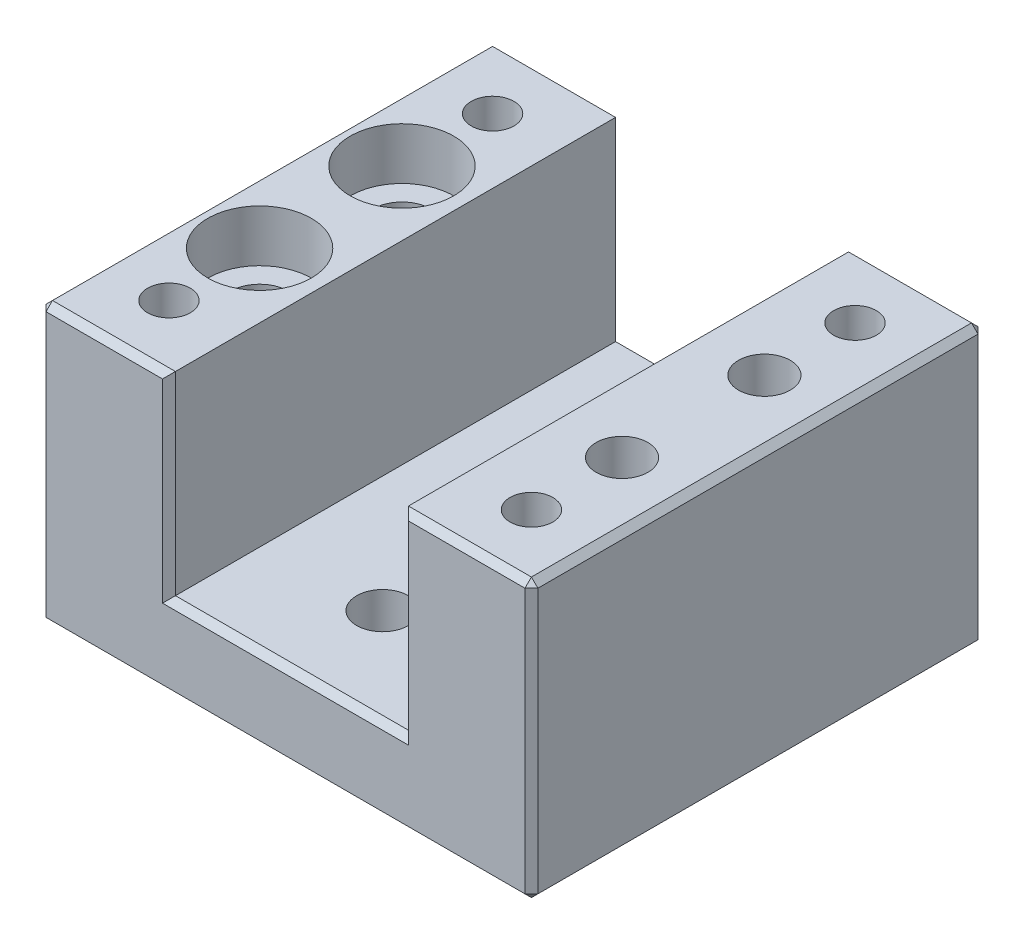
SolidWorks part; units mm, degrees
ref_plane "前视基准面" through (0, 0, 0) normal (0, 0, 1) x (1, 0, 0)
ref_plane "上视基准面" through (0, 0, 0) normal (0, 1, 0) x (1, 0, 0)
ref_plane "右视基准面" through (0, 0, 0) normal (1, 0, 0) x (0, 0, -1)
sketch "草图1" plane through (0, 0, 0) normal (0, 0, 1) x (1, 0, 0)
  line L1 (0, 0) -> (38, 0)
  line L2 (0, 0) -> (0, 6.45)
  line L3 (0, 6.45) -> (38, 6.45)
  line L4 (38, 0) -> (38, 6.45)
  dimension "D1" = 6.45
  dimension "D2" = 38
extrude "凸台-拉伸1" add sketch "草图1" along normal blind 35
sketch "草图2" plane through (0, 6.45, 0) normal (0, 1, 0) x (1, 0, 0)
  line L0 (38, -35) -> (0, -35) construction
  line L1 (0, 0) -> (10, 0)
  line L2 (0, 0) -> (0, -35)
  line L3 (0, -35) -> (10, -35)
  line L4 (10, 0) -> (10, -35)
  line L6 (38, -35) -> (28, -35)
  line L7 (38, -35) -> (38, 0)
  line L8 (38, 0) -> (28, 0)
  line L9 (28, -35) -> (28, 0)
  dimension "D1" = 10
  dimension "D2" = 10
extrude "凸台-拉伸2" add sketch "草图2" along normal blind 15
hole_wizard "M4 六角凹头螺钉的柱形沉头孔1" positions "草图4" profile "草图3" counterbore size "M4" standard "ISO" end condition through all
sketch "草图4" plane through (0, 21.45, 0) normal (0, 1, 0) x (-1, 0, 0)
  line L0 (0, 35) -> (-10, 35) construction
  line L1 (0, 0) -> (0, 35) construction
  point P0 (-5, 23)
  dimension "D1" = 12
  dimension "D2" = 5
sketch "草图3" plane through (5, 21.45, 23) normal (1, 0, 0) x (0, 0, 1)
  line L0 (0, 0) -> (0, 21.45)
  line L1 (0, 21.45) -> (2.25, 21.45)
  line L3 (2.25, 21.45) -> (2.25, 4)
  line L4 (2.25, 4) -> (4, 4)
  line L5 (4, 4) -> (4, 0)
  line L7 (4, 0) -> (0, 0)
  line L11 (0, -6.35) -> (0, 107.95) construction
  dimension "通孔孔直径" = 4.5
  dimension "通孔孔深度" = 21.45
  dimension "柱形沉头孔直径" = 8
  dimension "柱形沉头孔深度" = 4
pattern_linear "阵列(线性)1" count 2 spacing 11 along (0, 0, -1) of "M4 六角凹头螺钉的柱形沉头孔1"
sketch "草图5" plane through (0, 6.45, 0) normal (0, 1, 0) x (1, 0, 0)
  line L0 (19, -1035) -> (19, 48965) construction
  line L1 (28, -35) -> (10, -35) construction
  line L2 (28, 0) -> (10, 0) construction
  circle A0 centre (19, -27.5) radius 2
  circle A1 centre (19, -7.5) radius 2
  point P5 (19, -35)
  dimension "D1" = 4
  dimension "D2" = 7.5
  dimension "D3" = 7.5
extrude "切除-拉伸1" cut sketch "草图5" against normal through all
sketch "草图6" plane through (0, 21.45, 0) normal (0, 1, 0) x (1, 0, 0)
  line L0 (-995, -23) -> (49005, -23) construction
  line L1 (-995, -12) -> (49005, -12) construction
  line L2 (33, -1035) -> (33, 48965) construction
  line L3 (28, -35) -> (38, -35) construction
  circle A0 centre (33, -23) radius 2
  circle A1 centre (33, -12) radius 2
  point P11 (33, -35)
  dimension "D1" = 4
extrude "切除-拉伸2" cut sketch "草图6" against normal through all
hole_wizard "M4 螺纹孔1" positions "草图8" profile "草图7" tap size "M4" standard "ISO"
sketch "草图8" plane through (0, 21.45, 0) normal (0, 1, 0) x (-1, 0, 0)
  line L0 (0, 0) -> (0, 35) construction
  line L1 (0, 35) -> (-10, 35) construction
  point P0 (-5, 30)
  dimension "D1" = 5
  dimension "D2" = 5
sketch "草图7" plane through (5, 21.45, 30) normal (1, 0, 0) x (0, 0, 1)
  line L0 (0, 0) -> (0, 11.0914)
  line L1 (0, 11.0914) -> (1.65, 10.1)
  line L2 (1.65, 10.1) -> (1.65, 0)
  line L5 (1.65, 0) -> (0, 0)
  line L10 (0, 11.0914) -> (-1.65, 10.1) construction
  line L11 (0, -6.35) -> (0, 107.95) construction
  dimension "螺纹孔钻头直径" = 3.3
  dimension "螺纹孔钻头深度" = 10.1
  dimension "导头角度" = 118
cosmetic thread "孔螺蚊线1" parameters "D1"=8, "D2"=4
pattern_linear "阵列(线性)2" count 2 spacing 28 along (1, 0, 0) count 2 spacing 25 along (0, 0, -1) of "M4 螺纹孔1"
chamfer "倒角1" distance 0.5 angle 45 20 edges at (5, 21.45, 35) (28, 13.95, 35) (33, 21.45, 35) (19, 0, 0) (19, 0, 35) (38, 0, 17.5) (38, 10.725, 0) (38, 10.725, 35) (38, 21.45, 17.5) (33, 21.45, 0) (28, 13.95, 0) (5, 21.45, 0) (0, 21.45, 17.5) (0, 10.725, 0) (0, 10.725, 35) (0, 0, 17.5)
